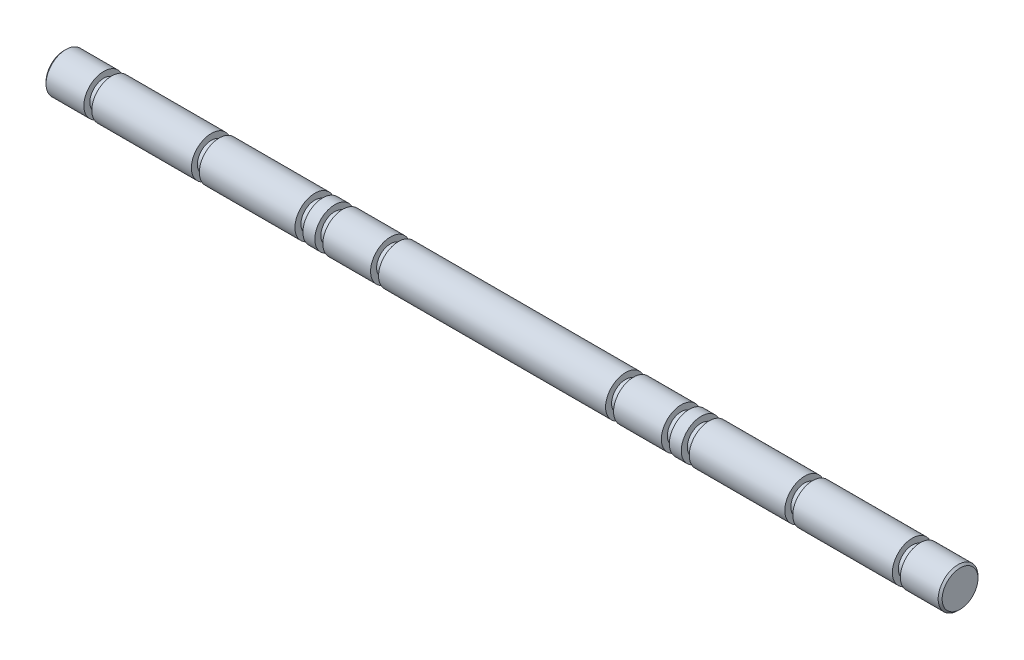
SolidWorks part; units mm, degrees
ref_plane "前视基准面" through (0, 0, 0) normal (0, 0, 1) x (1, 0, 0)
ref_plane "上视基准面" through (0, 0, 0) normal (0, 1, 0) x (1, 0, 0)
ref_plane "右视基准面" through (0, 0, 0) normal (1, 0, 0) x (0, 0, -1)
sketch "草图4" plane through (0, 0, 0) normal (1, 0, 0) x (0, 0, -1)
  circle A0 centre (0, 0) radius 5
  dimension "D1" = 10
extrude "凸台-拉伸4" add sketch "草图4" along normal blind 57
sketch "草图5" plane through (0, 0, 0) normal (-1, 0, 0) x (0, 0, 1)
  circle A0 centre (0, 0) radius 3.5
  dimension "D1" = 7
extrude "凸台-拉伸5" add sketch "草图5" along normal blind 2
sketch "草图6" plane through (-2, 0, 0) normal (-1, 0, 0) x (0, 0, 1)
  circle A0 centre (0, 0) radius 5
  dimension "D1" = 10
extrude "凸台-拉伸6" add sketch "草图6" along normal blind 12
sketch "草图7" plane through (57, 0, 0) normal (1, 0, 0) x (0, 0, -1)
  circle A0 centre (0, 0) radius 3.5
  dimension "D1" = 7
extrude "凸台-拉伸7" add sketch "草图7" along normal blind 2
sketch "草图8" plane through (59, 0, 0) normal (1, 0, 0) x (0, 0, -1)
  circle A0 centre (0, 0) radius 5
  dimension "D1" = 10
extrude "凸台-拉伸8" add sketch "草图8" along normal blind 12
sketch "草图9" plane through (71, 0, 0) normal (1, 0, 0) x (0, 0, -1)
  circle A0 centre (0, 0) radius 3.5
  dimension "D1" = 7
extrude "凸台-拉伸9" add sketch "草图9" along normal blind 2
sketch "草图10" plane through (73, 0, 0) normal (1, 0, 0) x (0, 0, -1)
  circle A0 centre (0, 0) radius 5
  dimension "D1" = 10
extrude "凸台-拉伸10" add sketch "草图10" along normal blind 3
sketch "草图11" plane through (76, 0, 0) normal (1, 0, 0) x (0, 0, -1)
  circle A0 centre (0, 0) radius 3.5
  dimension "D1" = 7
extrude "凸台-拉伸11" add sketch "草图11" along normal blind 2
sketch "草图12" plane through (78, 0, 0) normal (1, 0, 0) x (0, 0, -1)
  circle A0 centre (0, 0) radius 5
  dimension "D1" = 10
extrude "凸台-拉伸12" add sketch "草图12" along normal blind 24
sketch "草图13" plane through (102, 0, 0) normal (1, 0, 0) x (0, 0, -1)
  circle A0 centre (0, 0) radius 3.5
  dimension "D1" = 7
extrude "凸台-拉伸13" add sketch "草图13" along normal blind 2
sketch "草图14" plane through (104, 0, 0) normal (1, 0, 0) x (0, 0, -1)
  circle A0 centre (0, 0) radius 5
  dimension "D1" = 10
extrude "凸台-拉伸14" add sketch "草图14" along normal blind 25
sketch "草图15" plane through (129, 0, 0) normal (1, 0, 0) x (0, 0, -1)
  circle A0 centre (0, 0) radius 3.5
  dimension "D1" = 7
extrude "凸台-拉伸15" add sketch "草图15" along normal blind 2
sketch "草图16" plane through (131, 0, 0) normal (1, 0, 0) x (0, 0, -1)
  circle A0 centre (0, 0) radius 5
  dimension "D1" = 10
extrude "凸台-拉伸16" add sketch "草图16" along normal blind 10
sketch "草图33" plane through (-14, 0, 0) normal (-1, 0, 0) x (0, 0, 1)
  circle A0 centre (0, 0) radius 3.5
  dimension "D1" = 7
extrude "凸台-拉伸25" add sketch "草图33" along normal blind 2
sketch "草图34" plane through (-16, 0, 0) normal (-1, 0, 0) x (0, 0, 1)
  circle A0 centre (0, 0) radius 5
  dimension "D1" = 10
extrude "凸台-拉伸26" add sketch "草图34" along normal blind 3
sketch "草图35" plane through (-19, 0, 0) normal (-1, 0, 0) x (0, 0, 1)
  circle A0 centre (0, 0) radius 3.5
  dimension "D1" = 7
extrude "凸台-拉伸27" add sketch "草图35" along normal blind 2
sketch "草图36" plane through (-21, 0, 0) normal (-1, 0, 0) x (0, 0, 1)
  circle A0 centre (0, 0) radius 5
  dimension "D1" = 10
extrude "凸台-拉伸28" add sketch "草图36" along normal blind 24
sketch "草图37" plane through (-45, 0, 0) normal (-1, 0, 0) x (0, 0, 1)
  circle A0 centre (0, 0) radius 3.5
  dimension "D1" = 7
extrude "凸台-拉伸29" add sketch "草图37" along normal blind 2
sketch "草图38" plane through (-47, 0, 0) normal (-1, 0, 0) x (0, 0, 1)
  circle A0 centre (0, 0) radius 5
  dimension "D1" = 10
extrude "凸台-拉伸30" add sketch "草图38" along normal blind 25
sketch "草图39" plane through (-72, 0, 0) normal (-1, 0, 0) x (0, 0, 1)
  circle A0 centre (0, 0) radius 3.5
  dimension "D1" = 7
extrude "凸台-拉伸31" add sketch "草图39" along normal blind 2
sketch "草图40" plane through (-74, 0, 0) normal (-1, 0, 0) x (0, 0, 1)
  circle A0 centre (0, 0) radius 5
  dimension "D1" = 10
extrude "凸台-拉伸32" add sketch "草图40" along normal blind 10
chamfer "倒角1" distance 0.5 angle 45 2 edges at (141, 0, -5) (-84, 0, 5)
